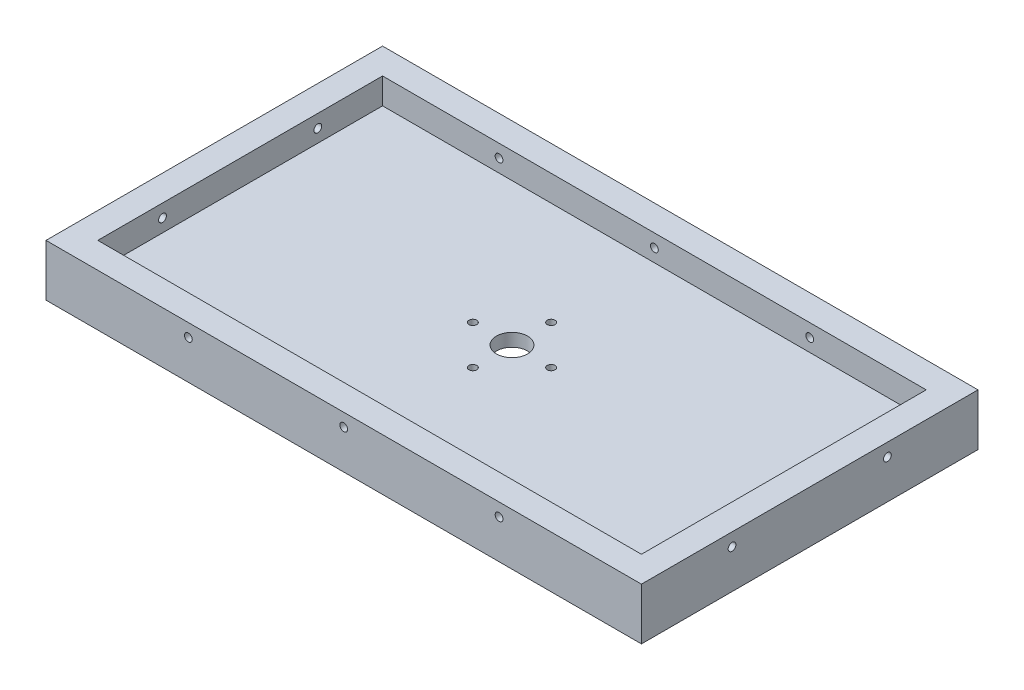
SolidWorks part; units mm, degrees
ref_plane "Front Plane" through (0, 0, 0) normal (0, 0, 1) x (1, 0, 0)
ref_plane "Top Plane" through (0, 0, 0) normal (0, 1, 0) x (1, 0, 0)
ref_plane "Right Plane" through (0, 0, 0) normal (1, 0, 0) x (0, 0, -1)
sketch "Sketch1" plane through (0, 0, 0) normal (0, 1, 0) x (1, 0, 0)
  line L0 (0, 0) -> (210, 0)
  line L1 (210, 0) -> (210, -110)
  line L2 (210, -110) -> (0, -110)
  line L3 (0, -110) -> (0, 0)
extrude "Boss-Extrude1" add sketch "Sketch1" along normal blind 10
sketch "Sketch2" plane through (0, 0, 0) normal (0, -1, 0) x (-1, 0, 0)
  line L0 (0, -55) -> (-210, -55)
  line L1 (0, 0) -> (0, -110) construction
  line L2 (-210, -110) -> (-210, 0) construction
  circle A1 centre (-105, -55) radius 25
extrude "Cut-Extrude1" cut sketch "Sketch2" against normal blind 5 contours L0 A1 | L0 A1
sketch "Sketch3" plane through (0, 5, 0) normal (0, -1, 0) x (-1, 0, 0)
  circle A0 centre (-105, -55) radius 15.1289
  circle A1 centre (-105, -70.1289) radius 1.5
  circle A2 centre (-120.1289, -55) radius 1.5
  circle A3 centre (-105, -39.8711) radius 1.5
  circle A4 centre (-89.8711, -55) radius 1.5
extrude "Cut-Extrude2" cut sketch "Sketch3" against normal blind 5 contours A2 | A1 | A3 | A4
sketch "Sketch4" plane through (0, 5, 0) normal (0, -1, 0) x (-1, 0, 0)
  circle A0 centre (-105, -55) radius 6
extrude "Cut-Extrude3" cut sketch "Sketch4" against normal blind 5
sketch "Sketch5" plane through (0, 0, 0) normal (0, -1, 0) x (-1, 0, 0)
  circle A0 centre (-105, -55) radius 30
extrude "Cut-Extrude4" cut sketch "Sketch5" against normal blind 5
sketch "Sketch10" plane through (0, 0, 0) normal (0, -1, 0) x (-1, 0, 0)
  line L0 (0, -110) -> (-210, -110)
  line L1 (10, -110) -> (10, 10)
  line L2 (10, 10) -> (-220, 10)
  line L3 (-220, 10) -> (-220, -120)
  line L4 (-220, -120) -> (10, -120)
  line L5 (10, -120) -> (10, -110)
  line L6 (-210, -110) -> (-210, 0)
  line L7 (-210, 0) -> (0, 0)
  line L8 (0, 0) -> (0, -110)
extrude "Boss-Extrude2" add sketch "Sketch10" against normal blind 20
sketch "Sketch11" plane through (-10, 0, 0) normal (-1, 0, 0) x (0, 0, 1)
  line L0 (-10, 20) -> (-10, 10)
  line L1 (-10, 20) -> (-10, 0) construction
  line L2 (-10, 10) -> (-10, 15)
  line L3 (-10, 15) -> (120, 15)
  line L4 (120, 20) -> (120, 0) construction
  line L5 (55, 15) -> (85, 15)
  line L6 (55, 15) -> (25, 15)
  circle A0 centre (25, 15) radius 1.5
  circle A1 centre (85, 15) radius 1.5
extrude "Cut-Extrude6" cut sketch "Sketch11" against normal blind 300 contours A0 | A1
sketch "Sketch12" plane through (0, 0, 120) normal (0, 0, 1) x (1, 0, 0)
  line L0 (-10, 20) -> (-10, 10)
  line L1 (-10, 20) -> (-10, 0) construction
  line L2 (-10, 10) -> (-10, 15)
  line L3 (-10, 15) -> (220, 15)
  line L4 (220, 20) -> (220, 0) construction
  line L5 (105, 15) -> (165, 15)
  line L6 (105, 15) -> (45, 15)
  circle A0 centre (45, 15) radius 1.5
  circle A1 centre (165, 15) radius 1.5
  circle A2 centre (105, 15) radius 1.5
extrude "Cut-Extrude7" cut sketch "Sketch12" against normal blind 300 contours A0 | A2 | A1
